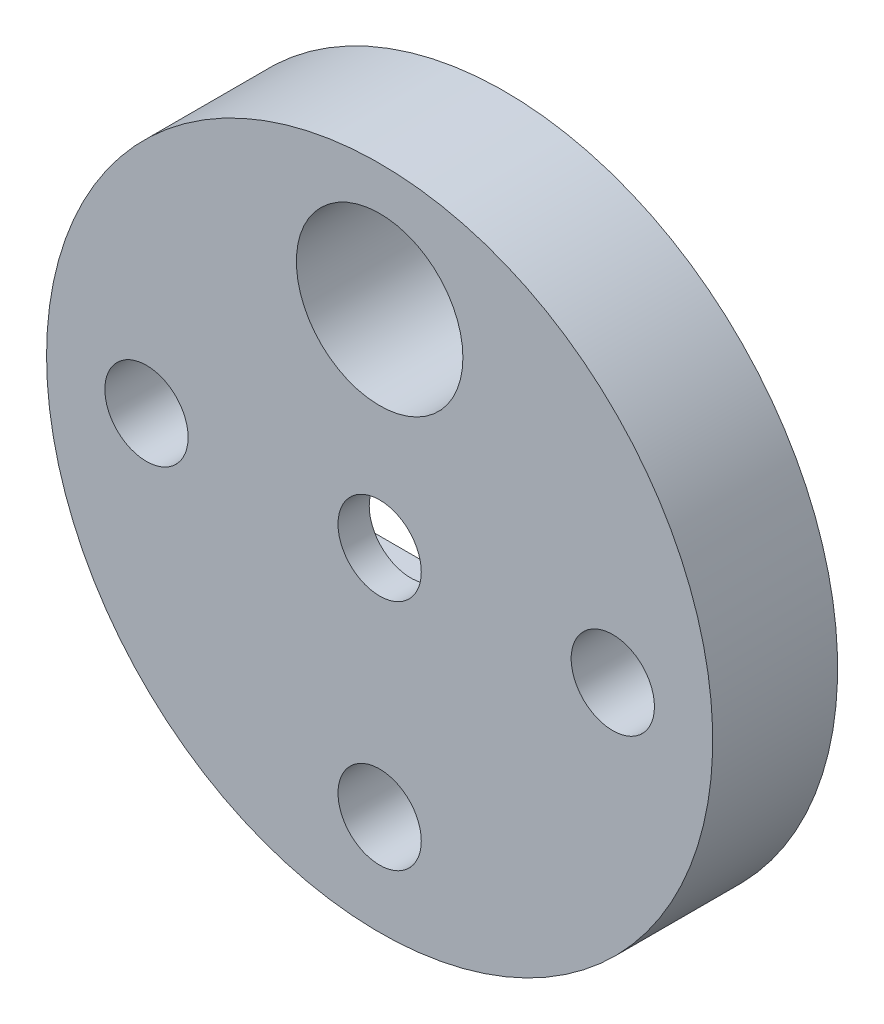
SolidWorks part; units mm, degrees
ref_plane "Front Plane" through (0, 0, 0) normal (0, 0, 1) x (1, 0, 0)
ref_plane "Top Plane" through (0, 0, 0) normal (0, 1, 0) x (1, 0, 0)
ref_plane "Right Plane" through (0, 0, 0) normal (1, 0, 0) x (0, 0, -1)
sketch "Sketch1" plane through (0, 0, 0) normal (0, 0, 1) x (1, 0, 0)
  circle A0 centre (0, 0) radius 25.4
  dimension "D1" = 50.8
extrude "Boss-Extrude1" add sketch "Sketch1" along normal blind 9.525 contours A0
sketch "Sketch2" plane through (0, 0, 0) normal (0, 0, 1) x (1, 0, 0)
  line L1 (-10.3188, 8.7313) -> (10.3187, 8.7313)
  line L2 (-10.3188, 8.7313) -> (-10.3187, -8.7312)
  line L3 (-10.3187, -8.7312) -> (10.3188, -8.7312)
  line L4 (10.3187, 8.7313) -> (10.3188, -8.7312)
  line L5 (-10.3188, 8.7313) -> (10.3188, -8.7312) construction
  line L6 (-10.3187, -8.7312) -> (10.3187, 8.7313) construction
  point P0 (0, 0)
  dimension "D1" = 20.6375
  dimension "D2" = 17.4625
extrude "Cut-Extrude1" cut sketch "Sketch2" along normal blind 7.1437 contours L1 L4 L3 L2
sketch "Sketch3" plane through (0, 0, 7.1437) normal (0, 0, -1) x (-1, 0, 0)
  circle A0 centre (0, 0) radius 3.175
  dimension "D1" = 6.35
extrude "Cut-Extrude9" cut sketch "Sketch3" against normal blind 15.5575 contours A0
sketch "Sketch5" plane through (0, 0, 9.525) normal (0, 0, 1) x (1, 0, 0)
  circle A0 centre (0, 15.748) radius 6.35
  circle A1 centre (17.78, 0) radius 3.175
  circle A2 centre (0, -17.7689) radius 3.175
  circle A3 centre (-17.78, 0) radius 3.175
  dimension "D1" = 12.7
  dimension "D2" = 6.35
  dimension "D3" = 6.35
  dimension "D4" = 6.35
  dimension "D5" = 15.748
  dimension "D6" = 17.7689
  dimension "D7" = 17.78
  dimension "D8" = 17.78
extrude "Cut-Extrude10" cut sketch "Sketch5" against normal blind 15.5575 contours A2 | A3 | A0 | A1
